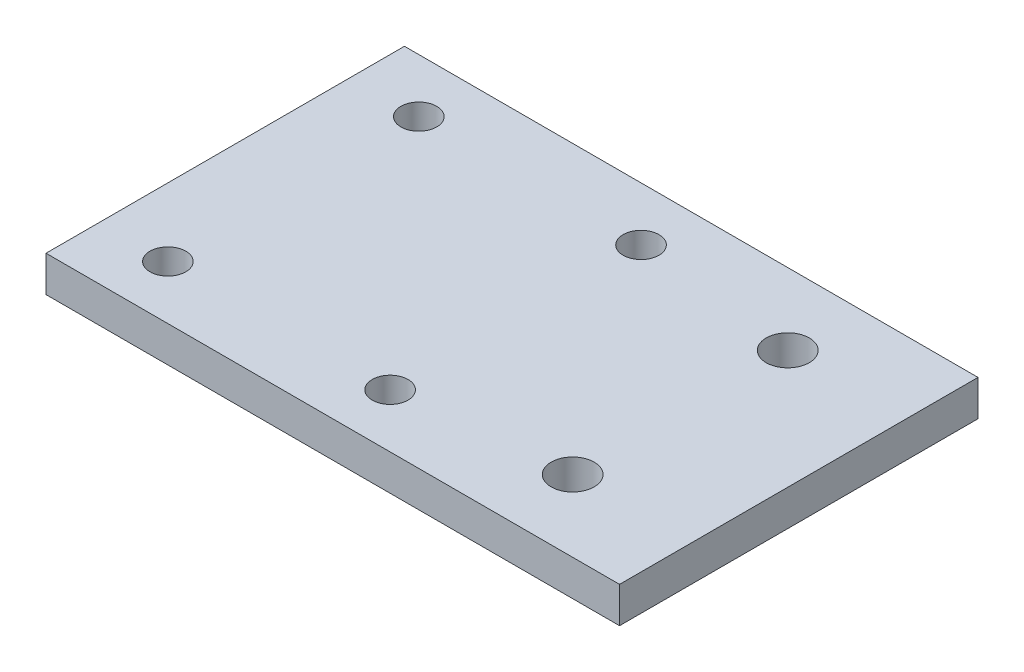
SolidWorks part; units mm, degrees
ref_plane "Front Plane" through (0, 0, 0) normal (0, 0, 1) x (1, 0, 0)
ref_plane "Top Plane" through (0, 0, 0) normal (0, 1, 0) x (1, 0, 0)
ref_plane "Right Plane" through (0, 0, 0) normal (1, 0, 0) x (0, 0, -1)
sketch "Sketch2" plane through (0, 0, 0) normal (0, 1, 0) x (1, 0, 0)
  line L1 (0, 0) -> (80, 0)
  line L2 (0, 0) -> (0, 50)
  line L3 (0, 50) -> (80, 50)
  line L4 (80, 0) -> (80, 50)
  circle A0 centre (63.4615, 10) radius 3
  circle A1 centre (63.4615, 40) radius 3
  dimension "D4" = 6
  dimension "D5" = 6
  dimension "D1" = 50
  dimension "D2" = 80
  dimension "D3" = 10
  dimension "D6" = 10
extrude "Boss-Extrude1" add sketch "Sketch2" along normal blind 5
sketch "Sketch3" plane through (0, 5, 0) normal (0, 1, 0) x (1, 0, 0)
  circle A0 centre (40.5, 7.5) radius 2.5
  circle A1 centre (9.5, 7.5) radius 2.5
  circle A2 centre (40.5, 42.5) radius 2.5
  circle A3 centre (9.5, 42.5) radius 2.5
extrude "Cut-Extrude1" cut sketch "Sketch3" against normal blind 10
